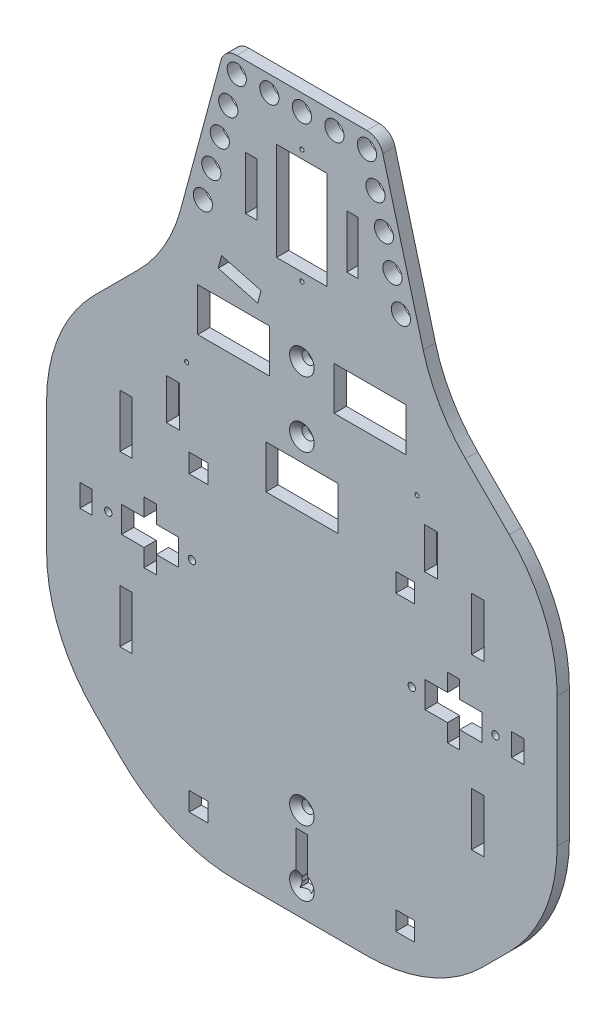
SolidWorks part; units mm, degrees
other "Popis1"
sketch "Skica4" plane through (-62.5, 107.5, 3) normal (-0.0791, 0.0312, 0.9964) x (0.9969, 0.0058, 0.079)
sketch "Skica5" plane through (-62.5, 107.5, 3) normal (-0.0791, 0.0312, 0.9964) x (0.9969, 0.0058, 0.079)
sketch "Skica6" plane through (-62.5, 112.5, 3) normal (-0.0791, 0.0312, 0.9964) x (0.9969, 0.0058, 0.079)
sketch "Skica7" plane through (-62.5, 112.5, 3) normal (-0.0791, 0.0312, 0.9964) x (0.9969, 0.0058, 0.079)
ref_plane "Přední rovina" through (0, 0, 0) normal (0, 0, 1) x (1, 0, 0)
ref_plane "Horní rovina" through (0, 0, 0) normal (0, 1, 0) x (1, 0, 0)
ref_plane "Pravá rovina" through (0, 0, 0) normal (1, 0, 0) x (0, 0, -1)
sketch "Skica1" plane through (0, 0, 0) normal (0, 0, 1) x (1, 0, 0)
  line L0 (-334.3708, 0) -> (16384.1714, 0) construction
  line L1 (0, -334.3708) -> (0, 16384.1714) construction
  line L2 (-44.3956, 7.5) -> (-44.3956, -7.5) construction
  line L3 (-62.5, -62.5) -> (62.5, -62.5) construction
  line L4 (-62.5, -62.5) -> (-62.5, 62.5) construction
  line L5 (-62.5, 62.5) -> (62.5, 62.5) construction
  line L6 (62.5, -62.5) -> (62.5, 62.5) construction
  line L7 (-62.5, -62.5) -> (62.5, 62.5) construction
  line L8 (-62.5, 62.5) -> (62.5, -62.5) construction
  line L9 (-44.3956, 7.5) -> (-61.3, 7.5) construction
  line L10 (-41.5478, 0) -> (-41.5478, 14.2) construction
  line L11 (-44.1478, 3.2) -> (-38.6478, 3.2)
  line L13 (-44.5478, 27.2) -> (-41.5478, 27.2)
  line L14 (-44.5478, 27.2) -> (-44.5478, 14.2)
  line L15 (-44.5478, 14.2) -> (-41.5478, 14.2)
  line L16 (-41.5478, 27.2) -> (-41.5478, 14.2)
  line L20 (-54.3478, 2.75) -> (-51.3478, 2.75)
  line L21 (-54.3478, 2.75) -> (-54.3478, -2.75)
  line L22 (-54.3478, -2.75) -> (-51.3478, -2.75)
  line L23 (-51.3478, 2.75) -> (-51.3478, -2.75)
  line L24 (-54.3478, 2.75) -> (-51.3478, -2.75) construction
  line L25 (-54.3478, -2.75) -> (-51.3478, 2.75) construction
  line L26 (-44.1478, 3.2) -> (-30.1478, 3.2) construction
  line L27 (-44.1478, 3.2) -> (-44.1478, -3.2)
  line L28 (-44.1478, -3.2) -> (-30.1478, -3.2) construction
  line L29 (-30.1478, 3.2) -> (-30.1478, -3.2)
  line L30 (-44.1478, 3.2) -> (-30.1478, -3.2) construction
  line L31 (-44.1478, -3.2) -> (-30.1478, 3.2) construction
  line L32 (-38.6478, -7.5) -> (-35.6478, -7.5)
  line L33 (-38.6478, -7.5) -> (-38.6478, 7.5) construction
  line L34 (-38.6478, 7.5) -> (-35.6478, 7.5)
  line L35 (-35.6478, -7.5) -> (-35.6478, 7.5) construction
  line L36 (-38.6478, -7.5) -> (-35.6478, 7.5) construction
  line L37 (-38.6478, 7.5) -> (-35.6478, -7.5) construction
  line L38 (-38.6478, 3.2) -> (-38.6478, 7.5)
  line L39 (-35.6478, 7.5) -> (-35.6478, 3.2)
  line L40 (-35.6478, 3.2) -> (-30.1478, 3.2)
  line L41 (-30.1478, -3.2) -> (-35.6478, -3.2)
  line L42 (-35.6478, -3.2) -> (-35.6478, -7.5)
  line L43 (-38.6478, -7.5) -> (-38.6478, -3.2)
  line L44 (-38.6478, -3.2) -> (-44.1478, -3.2)
  line L45 (-41.5478, -27.2) -> (-41.5478, -14.2)
  line L46 (-44.5478, -27.2) -> (-41.5478, -27.2)
  line L47 (-44.5478, -27.2) -> (-44.5478, -14.2)
  line L48 (-44.5478, -14.2) -> (-41.5478, -14.2)
  line L49 (-62.5, -32.5) -> (-62.5, 32.5)
  line L50 (-62.5, 32.5) -> (-32.5, 62.5)
  line L51 (-62.5, -32.5) -> (-32.5, -62.5)
  line L52 (-32.5, -62.5) -> (32.5, -62.5)
  line L54 (38.6478, -7.5) -> (35.6478, -7.5)
  line L55 (38.6478, -7.5) -> (38.6478, -3.2)
  line L56 (35.6478, -3.2) -> (35.6478, -7.5)
  line L57 (30.1478, -3.2) -> (35.6478, -3.2)
  line L58 (38.6478, -3.2) -> (44.1478, -3.2)
  line L59 (30.1478, 3.2) -> (30.1478, -3.2)
  line L60 (35.6478, 3.2) -> (30.1478, 3.2)
  line L61 (38.6478, 7.5) -> (35.6478, 7.5)
  line L62 (35.6478, 7.5) -> (35.6478, 3.2)
  line L63 (38.6478, 3.2) -> (38.6478, 7.5)
  line L64 (44.1478, 3.2) -> (44.1478, -3.2)
  line L65 (44.1478, 3.2) -> (38.6478, 3.2)
  line L66 (51.3478, 2.75) -> (51.3478, -2.75)
  line L67 (54.3478, -2.75) -> (51.3478, -2.75)
  line L68 (54.3478, 2.75) -> (54.3478, -2.75)
  line L69 (54.3478, 2.75) -> (51.3478, 2.75)
  line L70 (41.5478, 27.2) -> (41.5478, 14.2)
  line L71 (44.5478, 14.2) -> (41.5478, 14.2)
  line L72 (44.5478, 27.2) -> (44.5478, 14.2)
  line L73 (44.5478, 27.2) -> (41.5478, 27.2)
  line L74 (44.5478, -14.2) -> (41.5478, -14.2)
  line L75 (44.5478, -27.2) -> (44.5478, -14.2)
  line L76 (44.5478, -27.2) -> (41.5478, -27.2)
  line L77 (41.5478, -27.2) -> (41.5478, -14.2)
  line L78 (62.5, -32.5) -> (32.5, -62.5)
  line L79 (62.5, -32.5) -> (62.5, 32.5)
  line L80 (62.5, 32.5) -> (32.5, 62.5)
  line L81 (25.5, 59.1) -> (25.5, 48.5)
  line L82 (-8.8, 34.1) -> (8.8, 34.1)
  line L83 (-8.8, 34.1) -> (-8.8, 23.5)
  line L84 (-8.8, 23.5) -> (8.8, 23.5)
  line L85 (8.8, 34.1) -> (8.8, 23.5)
  line L86 (-8.8, 34.1) -> (8.8, 23.5) construction
  line L87 (-8.8, 23.5) -> (8.8, 34.1) construction
  line L88 (-25.5, 59.1) -> (-7.9, 59.1)
  line L89 (-25.5, 59.1) -> (-25.5, 48.5)
  line L90 (-25.5, 48.5) -> (-7.9, 48.5)
  line L91 (-7.9, 59.1) -> (-7.9, 48.5)
  line L92 (7.9, 59.1) -> (7.9, 48.5)
  line L93 (25.5, 48.5) -> (7.9, 48.5)
  line L94 (25.5, 59.1) -> (7.9, 59.1)
  line L95 (-6.2, 74.5) -> (-6.2, 98.5)
  line L96 (-6.2, 98.5) -> (6.2, 98.5)
  line L97 (6.2, 98.5) -> (6.2, 74.5)
  line L98 (6.2, 74.5) -> (-6.2, 74.5)
  line L99 (-11, 93) -> (-11, 80)
  line L100 (-11, 80) -> (-13.8, 80)
  line L101 (-13.8, 80) -> (-13.8, 93)
  line L102 (-13.8, 93) -> (-11, 93)
  line L107 (-20.4875, 65.0882) -> (-10.8282, 62.5)
  line L108 (-10.8282, 62.5) -> (-10, 65.591)
  line L109 (-10, 65.591) -> (-19.6593, 68.1792)
  line L110 (-19.6593, 68.1792) -> (-20.4875, 65.0882)
  line L111 (-6.2, 86.5) -> (6.2, 86.5) construction
  line L112 (-6.2, 86.5) -> (-11, 86.5) construction
  line L113 (11, 80) -> (13.8, 80)
  line L114 (11, 93) -> (11, 80)
  line L115 (13.8, 93) -> (11, 93)
  line L116 (13.8, 80) -> (13.8, 93)
  line L117 (30, 26) -> (33.2, 26)
  line L118 (-30, 36) -> (-33.2, 36)
  line L119 (-30, 36) -> (-30, 26)
  line L120 (-30, 26) -> (-33.2, 26)
  line L121 (-33.2, 36) -> (-33.2, 26)
  line L122 (33.2, 36) -> (33.2, 26)
  line L123 (30, 36) -> (33.2, 36)
  line L124 (30, 36) -> (30, 26)
  line L125 (-32.5, 62.5) -> (-19.0034, 112.5)
  line L126 (-19.0034, 112.5) -> (19.0034, 112.5)
  line L129 (0, 108.5) -> (7.97, 108.5) construction
  line L137 (32.5, 62.5) -> (19.0034, 112.5)
  line L138 (-15.94, 108.5) -> (-28.3568, 62.5) construction
  line L140 (-25.3, -51.5) -> (25.3, -51.5) construction
  line L141 (-25.3, -51.5) -> (-25.3, 20.23) construction
  line L142 (-25.3, 20.23) -> (25.3, 20.23) construction
  line L143 (25.3, -51.5) -> (25.3, 20.23) construction
  line L144 (-25.3, -51.5) -> (25.3, 20.23) construction
  line L145 (-25.3, 20.23) -> (25.3, -51.5) construction
  line L146 (-25.3, -15.635) -> (25.3, -15.635) construction
  line L147 (23, 22.53) -> (27.6, 22.53)
  line L148 (23, 22.53) -> (23, 17.93)
  line L149 (23, 17.93) -> (27.6, 17.93)
  line L150 (27.6, 22.53) -> (27.6, 17.93)
  line L151 (23, 22.53) -> (27.6, 17.93) construction
  line L152 (23, 17.93) -> (27.6, 22.53) construction
  line L153 (23, -49.2) -> (27.6, -49.2)
  line L154 (27.6, -53.8) -> (27.6, -49.2)
  line L155 (23, -53.8) -> (27.6, -53.8)
  line L156 (23, -53.8) -> (23, -49.2)
  line L157 (-23, -53.8) -> (-27.6, -53.8)
  line L158 (-23, -53.8) -> (-23, -49.2)
  line L159 (-27.6, -53.8) -> (-27.6, -49.2)
  line L160 (-23, -49.2) -> (-27.6, -49.2)
  line L161 (-23, 22.53) -> (-23, 17.93)
  line L162 (-23, 22.53) -> (-27.6, 22.53)
  line L163 (-27.6, 22.53) -> (-27.6, 17.93)
  line L164 (-23, 17.93) -> (-27.6, 17.93)
  line L165 (37.1478, 7.5) -> (37.1478, -7.5) construction
  circle A0 centre (-52.8478, 0) radius 11.3 construction
  circle A1 centre (0, 100.5) radius 0.5
  circle A3 centre (0, 72.5) radius 0.5
  circle A4 centre (0, 108.5) radius 2.35
  circle A5 centre (7.97, 108.5) radius 2.35
  circle A6 centre (15.94, 108.5) radius 2.35
  circle A7 centre (-15.94, 108.5) radius 2.35
  circle A8 centre (-7.97, 108.5) radius 2.35
  circle A9 centre (-15.94, 108.5) radius 2.35 construction
  circle A10 centre (-18.017, 100.8054) radius 2.35
  circle A11 centre (-20.094, 93.1108) radius 2.35
  circle A12 centre (-22.171, 85.4162) radius 2.35
  circle A13 centre (-24.2481, 77.7216) radius 2.35
  circle A14 centre (24.2481, 77.7216) radius 2.35
  circle A15 centre (22.171, 85.4162) radius 2.35
  circle A16 centre (20.094, 93.1108) radius 2.35
  circle A17 centre (18.017, 100.8054) radius 2.35
  circle A18 centre (47.3978, 0) radius 0.9
  circle A19 centre (26.8978, 0) radius 0.9
  circle A20 centre (-47.3978, 0) radius 0.9
  circle A21 centre (-26.8978, 0) radius 0.9
  point P4 (0, 0)
  point P15 (-52.8478, 0)
  point P17 (-37.1478, 0)
  point P27 (-37.1478, 0)
  point P46 (52.8478, 0)
  point P48 (0, 28.8)
  point P49 (0, -62.5)
  point P78 (0, 62.5)
  point P138 (0, 112.5)
  point P149 (-15.94, 108.5)
  point P156 (0, -15.635)
  dimension "D3" = 13
  dimension "D6" = 22.6
  dimension "D30" = 1
  dimension "D40" = 4.7
  dimension "D44" = 4
  dimension "D53" = 1.8
  dimension "D1" = 125
  dimension "D2" = 125
  dimension "D4" = 3
  dimension "D5" = 14.2
  dimension "D7" = 15
  dimension "D8" = 1.2
  dimension "D9" = 3
  dimension "D10" = 5.5
  dimension "D11" = 6.8
  dimension "D12" = 14
  dimension "D13" = 6.4
  dimension "D14" = 3
  dimension "D15" = 15
  dimension "D17" = 65
  dimension "D18" = 45
  dimension "D19" = 86
  dimension "D20" = 17.6
  dimension "D21" = 10.6
  dimension "D22" = 7.9
  dimension "D23" = 14.4
  dimension "D24" = 12.4
  dimension "D25" = 24
  dimension "D26" = 13
  dimension "D27" = 2.8
  dimension "D28" = 11
  dimension "D29" = 12
  dimension "D31" = 2
  dimension "D32" = 10
  dimension "D33" = 3.2
  dimension "D34" = 10
  dimension "D35" = 15
  dimension "D36" = 3.2
  dimension "D37" = 10
  dimension "D38" = 30
  dimension "D39" = 26
  dimension "D42" = 7.97
  dimension "D43" = 4
  dimension "D45" = 8
  dimension "D46" = 74.894
  dimension "D47" = 2
  dimension "D48" = 71.73
  dimension "D49" = 50.6
  dimension "D50" = 11
  dimension "D51" = 4.6
  dimension "D52" = 10.25
  dimension "D54" = 14.2
  dimension "D41" = 3
extrude "Přidat vysunutím1" add sketch "Skica1" along normal blind 3
sketch "Skica2" plane through (0, 0, 0) normal (0, 0, 1) x (1, 0, 0)
  line L0 (0, -1000) -> (0, 49000) construction
  line L1 (-1000, 0) -> (49000, 0) construction
  line L2 (8.8, 34.1) -> (-8.8, 34.1) construction
  circle A0 centre (0, 39.6) radius 1.5
  circle A1 centre (0, 55.6) radius 1.5
  circle A2 centre (0, -55.6) radius 1.5
  circle A3 centre (0, -39.6) radius 1.5
  dimension "D3" = 3
  dimension "D1" = 5.5
  dimension "D2" = 16
extrude "Odebrat vysunutím1" cut sketch "Skica2" along normal up to surface (3 mm away) up to face at (-25.3, -51.5, 3)
chamfer "Zkosení1" distance 1.5 angle 45 4 edges at (-1.5, -55.6, 3) (-1.5, -39.6, 3) (-1.5, 39.6, 3) (-1.5, 55.6, 3)
fillet "Zaoblit1" radius 40 8 edges at (-62.5, -32.5, 1.5) (-32.5, -62.5, 1.5) (32.5, -62.5, 1.5) (62.5, -32.5, 1.5) (62.5, 32.5, 1.5) (-62.5, 32.5, 1.5) (32.5, 62.5, 1.5) (-32.5, 62.5, 1.5)
fillet "Zaoblit2" radius 4 2 edges at (19.0034, 112.5, 1.5) (-19.0034, 112.5, 1.5)
sketch "Skica3" plane through (0, 0, 3) normal (0, 0, 1) x (1, 0, 0)
  line L0 (0, -965.9) -> (0, 49034.1) construction
  line L1 (8.8, 34.1) -> (-8.8, 34.1) construction
  line L2 (-11, 93) -> (-13.8, 93) construction
  line L3 (-1.4, -44.1) -> (1.4, -44.1)
  line L4 (-1.4, -44.1) -> (-1.4, -57.1)
  line L5 (-1.4, -57.1) -> (1.4, -57.1)
  line L6 (1.4, -44.1) -> (1.4, -57.1)
  line L7 (-13.8, 93) -> (-13.8, 80) construction
  circle A0 centre (-28.2, 41.3) radius 0.5
  circle A1 centre (28.2, 41.3) radius 0.5
  circle A2 centre (0, -55.6) radius 1.5 construction
  point P5 (0, 34.1)
  dimension "D1" = 1
  dimension "D2" = 28.2
  dimension "D3" = 7.2
extrude "Odebrat vysunutím2" cut sketch "Skica3" against normal through all
